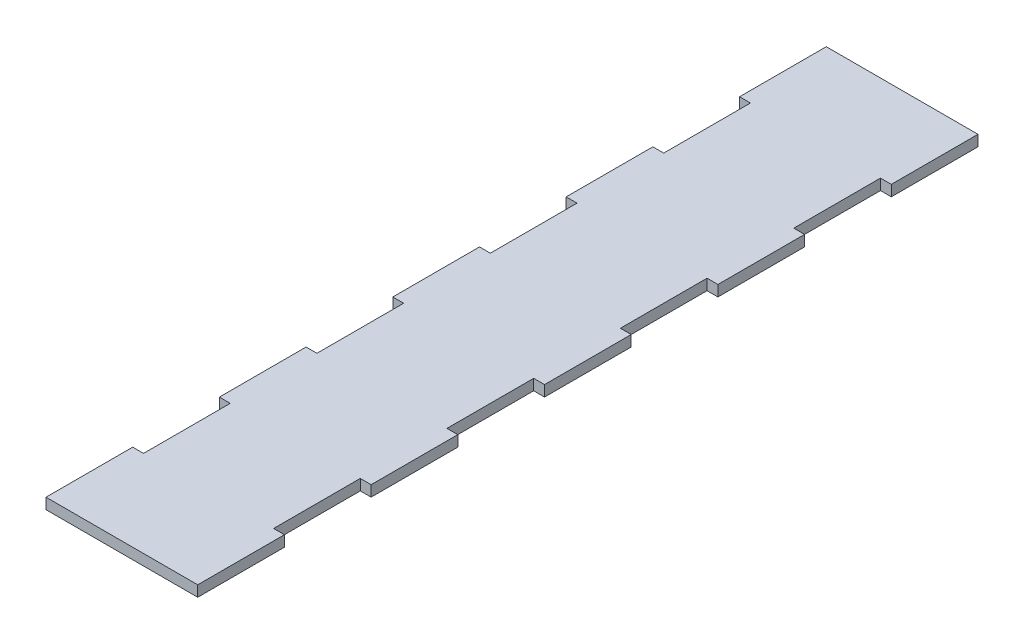
SolidWorks part; units mm, degrees
material "Pine"
ref_plane "Front Plane" through (0, 0, 0) normal (0, 0, 1) x (1, 0, 0)
ref_plane "Top Plane" through (0, 0, 0) normal (0, 1, 0) x (1, 0, 0)
ref_plane "Right Plane" through (0, 0, 0) normal (1, 0, 0) x (0, 0, -1)
sketch "Sketch1" plane through (0, 0, 0) normal (0, 0, 1) x (1, 0, 0)
  line L1 (38.1, -38.1) -> (-38.1, -38.1) construction
  line L2 (38.1, -38.1) -> (38.1, 38.1) construction
  line L3 (38.1, 38.1) -> (-38.1, 38.1)
  line L4 (-38.1, -38.1) -> (-38.1, 38.1) construction
  line L5 (38.1, -38.1) -> (-38.1, 38.1) construction
  line L6 (38.1, 38.1) -> (-38.1, -38.1) construction
  line L7 (-38.1, 38.1) -> (38.1, 38.1)
  line L8 (-38.1, 38.1) -> (-38.1, 44.45)
  line L9 (-38.1, 44.45) -> (38.1, 44.45)
  line L10 (38.1, 38.1) -> (38.1, 44.45)
  point P0 (0, 0)
  dimension "D1" = 76.2
  dimension "D2" = 6.35
extrude "Base Extrusion" add sketch "Sketch1" along normal blind 457.2 contours L3 L10 L9 L8
sketch "Sketch2" plane through (0, 44.45, 0) normal (0, 1, 0) x (1, 0, 0)
  line L0 (-44.45, -406.4) -> (-44.45, -355.6) construction
  line L1 (-38.1, -457.2) -> (-44.45, -457.2)
  line L2 (-38.1, -457.2) -> (-38.1, -406.4)
  line L3 (-38.1, -406.4) -> (-44.45, -406.4)
  line L4 (-44.45, -457.2) -> (-44.45, -406.4)
  line L5 (-44.45, -457.2) -> (-44.45, 0) construction
  line L6 (-44.45, -355.6) -> (-44.45, -304.8) construction
  line L7 (-44.45, -304.8) -> (-44.45, -254) construction
  line L8 (-44.45, -254) -> (-44.45, -203.2) construction
  line L9 (-44.45, -203.2) -> (-44.45, -152.4) construction
  line L10 (-44.45, -152.4) -> (-44.45, -101.6) construction
  line L11 (-44.45, -101.6) -> (-44.45, -50.8) construction
  line L12 (-44.45, -50.8) -> (-44.45, 0) construction
  dimension "D1" = 6.35
extrude "Tab" add sketch "Sketch2" against normal up to surface (6.35 mm away) up to face at (0, 38.1, 228.6)
pattern_linear "LPattern1" count 5 spacing 101.6 along (0, 0, -1) of "Tab"
mirror "Mirror2" about plane through (0, 0, 0) normal (1, 0, 0) of "LPattern1", "Tab"
